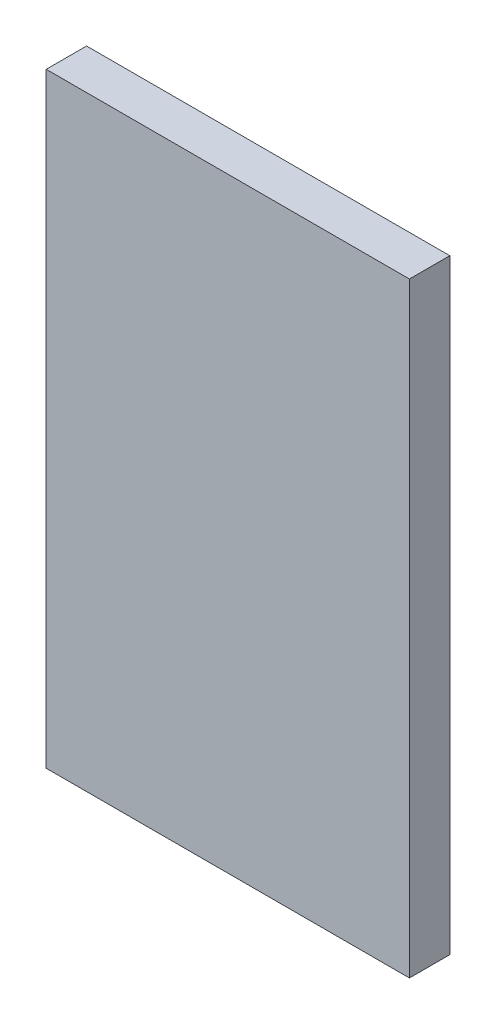
SolidWorks part; units mm, degrees
ref_plane "Front Plane" through (0, 0, 0) normal (0, 0, 1) x (1, 0, 0)
ref_plane "Top Plane" through (0, 0, 0) normal (0, 1, 0) x (1, 0, 0)
ref_plane "Right Plane" through (0, 0, 0) normal (1, 0, 0) x (0, 0, -1)
sketch "Sketch1" plane through (0, 0, 0) normal (0, 0, 1) x (1, 0, 0)
  line L1 (0, 0) -> (18, 0)
  line L2 (0, 0) -> (0, 30)
  line L3 (0, 30) -> (18, 30)
  line L4 (18, 0) -> (18, 30)
  dimension "D1" = 18
  dimension "D2" = 30
extrude "Boss-Extrude1" add sketch "Sketch1" along normal blind 2
